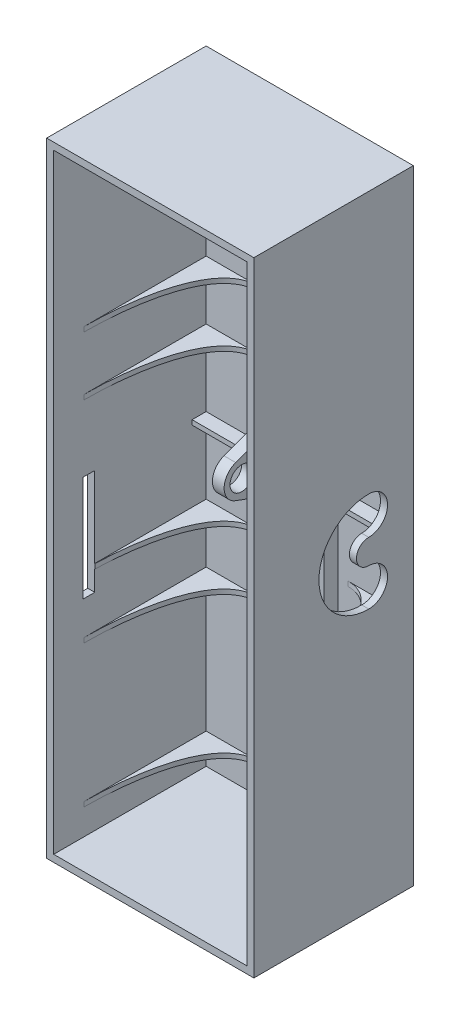
SolidWorks part; units mm, degrees
ref_plane "Front Plane" through (0, 0, 0) normal (0, 0, 1) x (1, 0, 0)
ref_plane "Top Plane" through (0, 0, 0) normal (0, 1, 0) x (1, 0, 0)
ref_plane "Right Plane" through (0, 0, 0) normal (1, 0, 0) x (0, 0, -1)
sketch "Sketch1" plane through (0, 0, 0) normal (0, 0, 1) x (1, 0, 0)
  line L0 (0, 263) -> (0, 0)
  line L1 (0, 0) -> (88.35, 0)
  line L3 (3, 3) -> (85.35, 3)
  line L7 (0, 263) -> (3, 263)
  line L8 (3, 3) -> (3, 263)
  line L11 (85.35, 3) -> (85.35, 263.0928)
  line L12 (85.35, 263.0928) -> (88.35, 263.0928)
  line L13 (88.35, 0) -> (88.35, 263.0928)
  dimension "D1" = 3
  dimension "D2" = 3
  dimension "D3" = 260
  dimension "D4" = 82.35
  dimension "D5" = 3
extrude "Boss-Extrude1" add sketch "Sketch1" along normal blind 68
sketch "Sketch2" plane through (0, 0, 0) normal (0, 0, 1) x (1, 0, 0)
  line L1 (0, 263) -> (88.35, 263)
  line L2 (0, 263) -> (0, 0)
  line L3 (0, 0) -> (88.35, 0)
  line L4 (88.35, 263) -> (88.35, 0)
extrude "Boss-Extrude2" add sketch "Sketch2" along normal blind 3
ref_plane "Plane1" through (34.175, 0, 0) normal (1, 0, 0) x (0, 0, -1)
sketch "Sketch3" plane through (34.175, 0, 0) normal (1, 0, 0) x (0, 0, -1)
  line L2 (-21.5652, 140.0477) -> (-3, 146.8049)
  line L3 (-3, 3) -> (-3, 263) construction
  line L4 (-3, 146.8049) -> (-3, 119.1951)
  line L5 (-3, 119.1951) -> (-21.5652, 125.9523)
  line L7 (-68, 3) -> (-3, 3) construction
  arc A0 (-21.5652, 140.0477) -> (-21.5652, 125.9523) centre (-19, 133) ccw
  circle A1 centre (-19, 133) radius 5
  dimension "D2" = 15
  dimension "D5" = 10
  dimension "D1" = 16
  dimension "D3" = 130
  dimension "D4" = 70
extrude "Boss-Extrude3" add sketch "Sketch3" against normal blind 5
ref_plane "Plane2" through (54.175, 0, 0) normal (1, 0, 0) x (0, 0, -1)
sketch "Sketch6" plane through (54.175, 0, 0) normal (1, 0, 0) x (0, 0, -1)
  line L0 (-19, 138) -> (-3, 138)
  line L2 (-3, 138) -> (-3, 128)
  line L3 (-3, 128) -> (-19, 128)
  line L4 (-3, 263) -> (-3, 3) construction
  arc A0 (-19, 138) -> (-19, 128) centre (-19, 133) ccw
  circle A1 centre (-19, 133) radius 5 construction
extrude "Boss-Extrude6" add sketch "Sketch6" along normal blind 8
hole_wizard "M6 Clearance Hole1" positions "Sketch7" profile "Sketch8" hole size "M6" standard "ISO"
sketch "Sketch7" plane through (54.175, 0, 0) normal (-1, 0, 0) x (0, 0, 1)
  arc A0 (19, 128) -> (19, 138) centre (19, 133) ccw construction
  point P0 (19, 133)
sketch "Sketch8" plane through (54.175, 133, 19) normal (0, 1, 0) x (0, 0, 1)
  line L0 (0, 0) -> (0, 8)
  line L1 (0, 8) -> (3.3, 8)
  line L2 (3.3, 8) -> (3.3, 0)
  line L5 (3.3, 0) -> (0, 0)
  line L11 (0, -6.35) -> (0, 107.95) construction
  dimension "Thru Hole Dia." = 6.6
  dimension "Thru Hole Depth" = 8
sketch "Sketch10" plane through (85.35, 0, 0) normal (-1, 0, 0) x (0, 0, 1)
  line L2 (3, 263) -> (3, 3) construction
  line L4 (19, 146.25) -> (19, 119.75) construction
  arc A0 (19, 146.25) -> (19, 119.75) centre (19, 133) cw construction
  arc A1 (19, 111.75) -> (19, 154.25) centre (19, 133) ccw
  arc A2 (19, 127.75) -> (19, 138.25) centre (19, 133) ccw
  arc A3 (19, 127.75) -> (19, 111.75) centre (19, 119.75) ccw
  arc A4 (19, 154.25) -> (19, 138.25) centre (19, 146.25) ccw
  point P5 (32.25, 133)
  point P20 (3, 133)
  dimension "D3" = 8
  dimension "D1" = 16
  dimension "D2" = 13.25
extrude "Cut-Extrude1" cut sketch "Sketch10" against normal up to next
sketch "Sketch11" plane through (0, 263, 0) normal (0, 1, 0) x (1, 0, 0)
  line L4 (0, 0) -> (0, -68)
  line L5 (88.35, 0) -> (0, 0)
  line L6 (88.35, -68) -> (88.35, 0)
  line L7 (0, -68) -> (88.35, -68)
  line L8 (0, 0) -> (0, -68)
  line L9 (88.35, 0) -> (0, 0)
  line L10 (88.35, -68) -> (88.35, 0)
  line L11 (0, -68) -> (88.35, -68)
  dimension "D1" = 0
extrude "Boss-Extrude7" add sketch "Sketch11" along normal blind 3
ref_plane "Plane4" through (44.175, 0, 0) normal (1, 0, 0) x (0, 0, -1)
sketch "Sketch13" plane through (0, 0, 3) normal (0, 0, 1) x (1, 0, 0)
  line L0 (3, 3) -> (3, 263) construction
  line L1 (3, 251.9797) -> (24.8525, 251.9797)
  line L2 (3, 251.9797) -> (3, 249.9797)
  line L3 (3, 249.9797) -> (24.8525, 249.9797)
  line L4 (24.8525, 251.9797) -> (24.8525, 249.9797)
  line L5 (3, 3) -> (3, 263) construction
  line L6 (3, 191.4189) -> (24.8525, 191.4189)
  line L7 (3, 191.4189) -> (3, 189.4189)
  line L8 (3, 189.4189) -> (24.8525, 189.4189)
  line L9 (24.8525, 191.4189) -> (24.8525, 189.4189)
  line L10 (3, 166.3498) -> (24.8525, 166.3498)
  line L11 (3, 166.3498) -> (3, 164.3498)
  line L12 (3, 164.3498) -> (24.8525, 164.3498)
  line L13 (24.8525, 166.3498) -> (24.8525, 164.3498)
  line L14 (3, 133) -> (85.35, 133) construction
  line L15 (85.35, 263) -> (85.35, 3) construction
  line L16 (3, 16.0203) -> (24.8525, 16.0203)
  line L17 (24.8525, 14.0203) -> (24.8525, 16.0203)
  line L18 (3, 14.0203) -> (24.8525, 14.0203)
  line L19 (3, 14.0203) -> (3, 16.0203)
  line L20 (3, 76.5811) -> (24.8525, 76.5811)
  line L21 (24.8525, 74.5811) -> (24.8525, 76.5811)
  line L22 (3, 74.5811) -> (24.8525, 74.5811)
  line L23 (3, 74.5811) -> (3, 76.5811)
  line L24 (3, 101.6502) -> (24.8525, 101.6502)
  line L25 (24.8525, 99.6502) -> (24.8525, 101.6502)
  line L26 (3, 99.6502) -> (24.8525, 99.6502)
  line L27 (3, 99.6502) -> (3, 101.6502)
  dimension "D1" = 2
extrude "Boss-Extrude8" add sketch "Sketch13" along normal blind 52
sketch "Sketch14" plane through (0, 14.0203, 0) normal (0, -1, 0) x (1, 0, 0)
  line L0 (3, 3) -> (24.8525, 3) construction
  line L1 (3, 55) -> (3, 3) construction
  line L2 (24.8525, 3) -> (24.8525, 55)
  line L3 (24.8525, 55) -> (3, 55)
  spline S0 degree 3 poles (3, 55) (3, 38.0721) (6.2716, 3) (24.8525, 3) knots 0 0 0 0 1 1 1 1
extrude "Cut-Extrude2" cut sketch "Sketch14" against normal up to surface (237.9595 mm away) up to face at (13.9263, 251.9797, 29)
mirror "Mirror3" about plane through (44.175, 0, 0) normal (1, 0, 0) of "Boss-Extrude8", "Cut-Extrude2"
sketch "Sketch15" plane through (0, 0, 3) normal (0, 0, 1) x (1, 0, 0)
  line L0 (85.35, 263) -> (3, 263) construction
  line L1 (30.675, 263) -> (32.675, 263)
  line L2 (30.675, 263) -> (30.675, 3)
  line L3 (30.675, 3) -> (32.675, 3)
  line L4 (32.675, 263) -> (32.675, 3)
  line L5 (85.35, 3) -> (3, 3) construction
  line L6 (29.175, 119.1951) -> (34.175, 119.1951) construction
  line L7 (3, 263) -> (85.35, 263) construction
  line L8 (59.175, 263) -> (57.175, 263)
  line L9 (59.175, 263) -> (59.175, 3)
  line L10 (59.175, 3) -> (57.175, 3)
  line L11 (57.175, 263) -> (57.175, 3)
  line L12 (62.175, 128) -> (54.175, 128) construction
  line L13 (29.175, 119.1951) -> (29.175, 146.8049) construction
  line L14 (29.175, 134) -> (3, 134)
  line L15 (29.175, 134) -> (29.175, 132)
  line L16 (29.175, 132) -> (3, 132)
  line L17 (3, 134) -> (3, 132)
  line L18 (3, 101.6502) -> (3, 164.3498) construction
  line L19 (62.175, 128) -> (62.175, 138) construction
  line L20 (62.175, 134) -> (85.35, 134)
  line L21 (62.175, 134) -> (62.175, 132)
  line L22 (62.175, 132) -> (85.35, 132)
  line L23 (85.35, 134) -> (85.35, 132)
  line L24 (85.35, 263) -> (85.35, 3) construction
  line L25 (29.175, 140.0477) -> (29.175, 125.9523) construction
  point P10 (31.675, 119.1951)
  point P11 (31.675, 3)
  point P18 (58.175, 3)
  point P21 (58.175, 128)
  point P38 (62.175, 133)
  point P39 (29.175, 133)
  dimension "D1" = 2
extrude "Boss-Extrude9" add sketch "Sketch15" along normal blind 6
sketch "Sketch16" plane through (0, 0, 3) normal (0, 0, 1) x (1, 0, 0)
  line L1 (36.675, 258) -> (51.675, 258)
  line L2 (36.675, 258) -> (36.675, 208)
  line L3 (36.675, 208) -> (51.675, 208)
  line L4 (51.675, 258) -> (51.675, 208)
  line L5 (54.175, 138) -> (54.175, 128) construction
  line L7 (34.175, 133) -> (54.175, 133) construction
  line L8 (34.175, 119.1951) -> (34.175, 146.8049) construction
  line L9 (36.675, 58) -> (51.675, 58)
  line L10 (51.675, 8) -> (51.675, 58)
  line L11 (36.675, 8) -> (51.675, 8)
  line L12 (36.675, 8) -> (36.675, 58)
  line L13 (88.35, 266) -> (0, 266) construction
  point P10 (54.175, 133)
  point P11 (51.675, 233)
  point P20 (44.175, 266)
  point P21 (44.175, 258)
  dimension "D1" = 15
  dimension "D2" = 50
  dimension "D3" = 100
extrude "Boss-Extrude10" add sketch "Sketch16" along normal blind 4
hole_wizard "M6 Tapped Hole2" positions "Sketch17" profile "Sketch18" tap size "M6" standard "ISO" end condition up to next
sketch "Sketch17" plane through (0, 0, 7) normal (0, 0, 1) x (1, 0, 0)
  line L0 (51.675, 258) -> (36.675, 258) construction
  line L1 (36.675, 208) -> (51.675, 208) construction
  line L2 (51.675, 58) -> (36.675, 58) construction
  line L3 (36.675, 8) -> (51.675, 8) construction
  point P0 (44.175, 250.24)
  point P2 (44.175, 215.76)
  point P4 (44.175, 50.24)
  point P6 (44.175, 15.76)
  point P18 (44.175, 8)
  dimension "D1" = 7.76
  dimension "D2" = 7.76
  dimension "D3" = 7.76
  dimension "D4" = 7.76
sketch "Sketch18" plane through (44.175, 250.24, 7) normal (1, 0, 0) x (0, -1, 0)
  line L0 (0, 0) -> (0, 7)
  line L1 (0, 7) -> (2.5, 7)
  line L2 (2.5, 7) -> (2.5, 0)
  line L5 (2.5, 0) -> (0, 0)
  line L11 (0, -6.35) -> (0, 107.95) construction
  dimension "Thru Tap Drill Dia." = 5
  dimension "Thru Tap Drill Depth" = 7
cosmetic thread "Hole Thread2" parameters "D2"=6
cosmetic thread "Hole Thread3" parameters "D2"=6
cosmetic thread "Hole Thread4" parameters "D2"=6
cosmetic thread "Hole Thread5" parameters "D2"=6
sketch "Sketch20" plane through (3, 0, 0) normal (1, 0, 0) x (0, 0, -1)
  line L0 (-68, 3) -> (-68, 263) construction
  line L1 (-55.5, 136) -> (-50.5, 136)
  line L2 (-55.5, 136) -> (-55.5, 91)
  line L3 (-55.5, 91) -> (-50.5, 91)
  line L4 (-50.5, 136) -> (-50.5, 91)
  line L6 (0, 266) -> (-68, 266) construction
  dimension "D1" = 45
  dimension "D2" = 12.5
  dimension "D3" = 5
  dimension "D4" = 175
extrude "Cut-Extrude4" cut sketch "Sketch20" against normal mid plane 20
